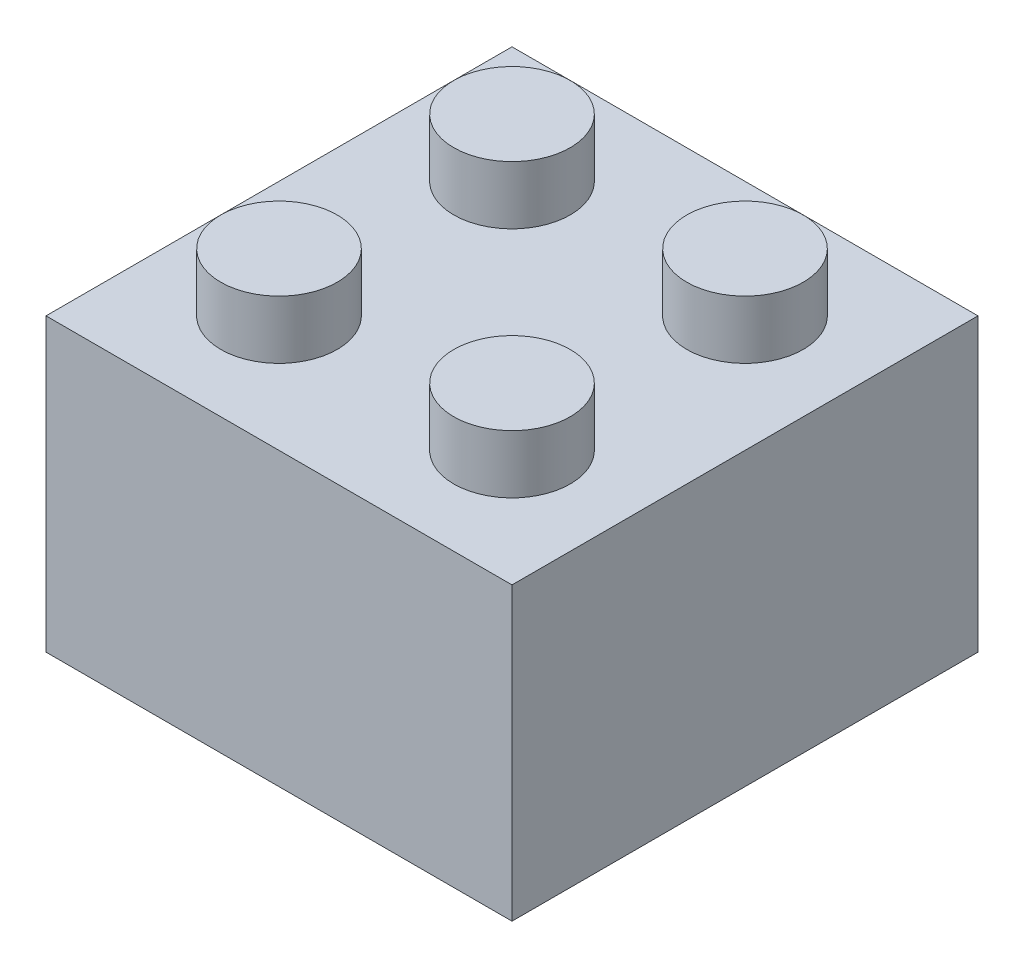
SolidWorks part; units mm, degrees
ref_plane "Front Plane" through (0, 0, 0) normal (0, 0, 1) x (1, 0, 0)
ref_plane "Top Plane" through (0, 0, 0) normal (0, 1, 0) x (1, 0, 0)
ref_plane "Right Plane" through (0, 0, 0) normal (1, 0, 0) x (0, 0, -1)
sketch "Sketch1" plane through (0, 0, 0) normal (0, 1, 0) x (1, 0, 0)
  line L1 (-8, 8) -> (8, 8)
  line L2 (-8, 8) -> (-8, -8)
  line L3 (-8, -8) -> (8, -8)
  line L4 (8, 8) -> (8, -8)
  line L5 (-8, 8) -> (8, -8) construction
  line L6 (-8, -8) -> (8, 8) construction
  point P0 (0, 0)
  dimension "D1" = 16
  dimension "D2" = 16
extrude "Boss-Extrude1" add sketch "Sketch1" along normal blind 10
sketch "Sketch2" plane through (0, 10, 0) normal (0, 1, 0) x (1, 0, 0)
  line L0 (-8, 8) -> (-8, -8) construction
  line L1 (8, 8) -> (-8, 8) construction
  line L2 (8, -8) -> (8, 8) construction
  line L3 (-8, -8) -> (8, -8) construction
  circle A0 centre (-4, 4) radius 2
  circle A1 centre (4, 4) radius 2
  circle A2 centre (-4, -4) radius 2
  circle A3 centre (4, -4) radius 2
  dimension "D1" = 4
  dimension "D2" = 4
  dimension "D3" = 4
  dimension "D4" = 4
  dimension "D5" = 4
extrude "Boss-Extrude2" add sketch "Sketch2" along normal blind 2
shell "Shell1" thickness 1
sketch "Sketch3" plane through (0, 9, 0) normal (0, -1, 0) x (1, 0, 0)
  circle A0 centre (0, 0) radius 2.7
  circle A1 centre (0, 0) radius 1.7
  dimension "D1" = 5.4
  dimension "D2" = 3.4
extrude "Boss-Extrude3" add sketch "Sketch3" along normal blind 9
